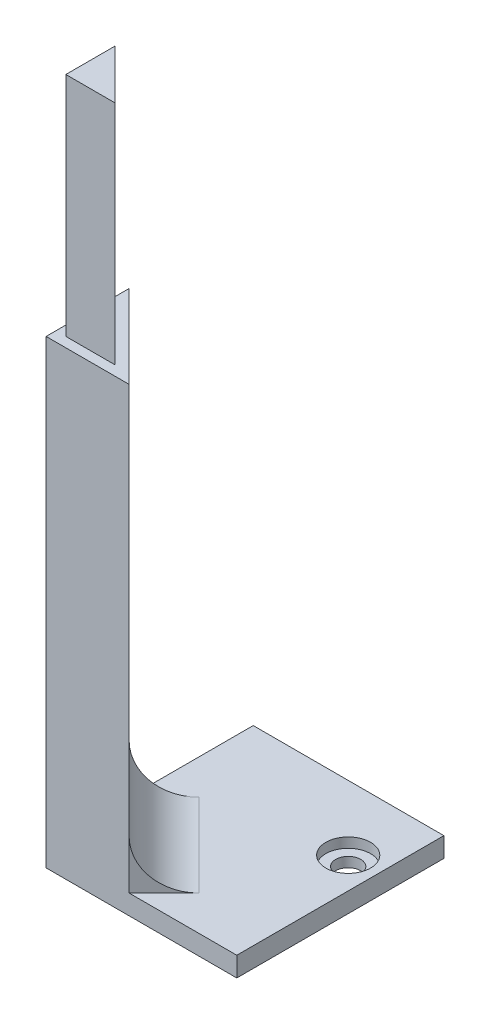
SolidWorks part; units mm, degrees
ref_plane "Front Plane" through (0, 0, 0) normal (0, 0, 1) x (1, 0, 0)
ref_plane "Top Plane" through (0, 0, 0) normal (0, 1, 0) x (1, 0, 0)
ref_plane "Right Plane" through (0, 0, 0) normal (1, 0, 0) x (0, 0, -1)
sketch "Sketch1" plane through (0, 0, 0) normal (0, 1, 0) x (1, 0, 0)
  line L9 (0, 0) -> (0, 15)
  line L35 (0, 0) -> (15, 0)
  line L50 (0, 15) -> (15, 0)
  point P0 (0, 0)
  point P5 (0, 0)
  point P6 (0, 0)
  point P9 (0, 0)
  point P10 (0, 0)
  dimension "D1" = 15
  dimension "D2" = 15
extrude "Boss-Extrude3" add sketch "Sketch1" along normal blind 320
sketch "Sketch8" plane through (0, 0, 0) normal (0, 0, 1) x (1, 0, 0)
  line L0 (0, 320) -> (0, 209)
  line L1 (0, 320) -> (0, 0) construction
  line L2 (0, 0) -> (15, 0) construction
  line L3 (0, 209) -> (15, 209)
  line L4 (15, 320) -> (15, 0) construction
  line L5 (15, 209) -> (15, 320)
  line L6 (15, 320) -> (0, 320)
  dimension "D1" = 209
extrude "Cut-Extrude4" cut sketch "Sketch8" against normal through all
sketch "Sketch9" plane through (0, 0, 0) normal (0, -1, 0) x (1, 0, 0)
  line L3 (-3, -22.2426) -> (-3, 3)
  line L4 (-3, 3) -> (22.2426, 3)
  line L5 (22.2426, 3) -> (-3, -22.2426)
extrude "Boss-Extrude5" add sketch "Sketch9" against normal blind 140
sketch "Sketch4" plane through (0, 0, 0) normal (0, -1, 0) x (1, 0, 0)
  line L0 (-3, 3) -> (55, 3)
  line L9 (55, 3) -> (55, -60)
  line L10 (55, -60) -> (-3, -60)
  line L11 (-3, -60) -> (-3, 3)
  circle A0 centre (45.59, -40.3) radius 3.8
  dimension "D3" = 7.6
  dimension "D4" = 9.41
  dimension "D1" = 58
  dimension "D2" = 63
  dimension "D6" = 43.3
extrude "Boss-Extrude4" add sketch "Sketch4" against normal blind 6
sketch "Sketch10" plane through (0, 6, 0) normal (0, 1, 0) x (1, 0, 0)
  line L0 (-3, 22.2426) -> (7.6066, 32.8492)
  line L1 (7.6066, 32.8492) -> (32.8492, 7.6066)
  line L2 (32.8492, 7.6066) -> (22.2426, -3)
  line L3 (-3, 22.2426) -> (22.2426, -3)
  dimension "D1" = 15
extrude "Boss-Extrude6" add sketch "Sketch10" along normal blind 15
sketch "Sketch11" plane through (12.6213, 0, 12.6213) normal (0.7071, 0, 0.7071) x (0.7071, 0, -0.7071)
  line L0 (13.6066, 21) -> (28.6066, 21)
  line L1 (28.6066, 21) -> (28.6066, 6)
  arc A0 (13.6066, 21) -> (28.6066, 6) centre (28.6066, 21) ccw
extrude "Cut-Extrude5" cut sketch "Sketch11" against normal through all
sketch "Sketch12" plane through (0, 6, 0) normal (0, 1, 0) x (1, 0, 0)
  circle A0 centre (45.59, 40.3) radius 6.8
  circle A1 centre (45.59, 40.3) radius 3.8 construction
  dimension "D1" = 3
extrude "Cut-Extrude6" cut sketch "Sketch12" against normal blind 3
